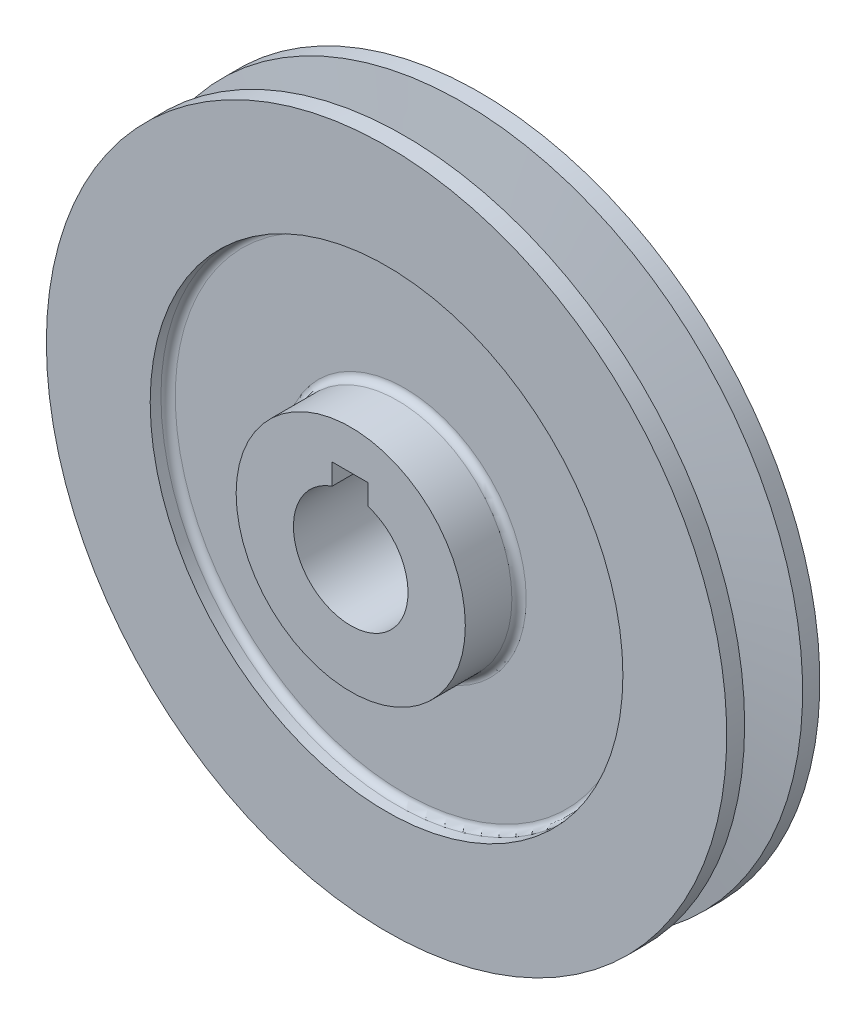
SolidWorks part; units mm, degrees
ref_plane "Front Plane" through (0, 0, 0) normal (0, 0, 1) x (1, 0, 0)
ref_plane "Top Plane" through (0, 0, 0) normal (0, 1, 0) x (1, 0, 0)
ref_plane "Right Plane" through (0, 0, 0) normal (1, 0, 0) x (0, 0, -1)
sketch "Sketch1" plane through (0, 0, 0) normal (0, 0, 1) x (1, 0, 0)
  circle A0 centre (0, 0) radius 47.5
  dimension "D1" = 95
extrude "Boss-Extrude1" add sketch "Sketch1" along normal blind 13
sketch "Sketch2" plane through (0, 0, 13) normal (0, 0, 1) x (1, 0, 0)
  circle A0 centre (0, 0) radius 33
  dimension "D1" = 66
extrude "Cut-Extrude1" cut sketch "Sketch2" against normal blind 2.5
sketch "Sketch3" plane through (0, 0, 0) normal (0, 0, -1) x (-1, 0, 0)
  circle A0 centre (0, 0) radius 33
  dimension "D1" = 66
extrude "Cut-Extrude2" cut sketch "Sketch3" against normal blind 2.5
sketch "Sketch4" plane through (0, 0, 2.5) normal (0, 0, -1) x (-1, 0, 0)
  circle A0 centre (0, 0) radius 16
  dimension "D1" = 32
extrude "Boss-Extrude2" add sketch "Sketch4" along normal blind 7.5
sketch "Sketch5" plane through (0, 0, 10.5) normal (0, 0, 1) x (1, 0, 0)
  circle A0 centre (0, 0) radius 16
  dimension "D1" = 32
extrude "Boss-Extrude3" add sketch "Sketch5" along normal blind 7.5
sketch "Sketch9" plane through (0, 0, -5) normal (0, 0, -1) x (-1, 0, 0)
  circle A0 centre (0, 0) radius 8
  dimension "D1" = 16
extrude "Cut-Extrude3" cut sketch "Sketch9" against normal through all
fillet "Fillet1" radius 1 1 edges at (-16, 0, 2.5)
fillet "Fillet2" radius 1 1 edges at (16, 0, 10.5)
sketch "Sketch12" plane through (0, 0, 0) normal (1, 0, 0) x (0, 0, -1)
  line L0 (-10.5, 47.5) -> (-8.5051, 33)
  line L1 (0, 47.5) -> (-13, 47.5) construction
  line L2 (-8.5051, 33) -> (-4.46, 33)
  line L3 (-4.46, 33) -> (-2.4034, 47.5)
  line L4 (-6.5, 33) -> (-6.5, 26.3279) construction
  line L8 (-31.2441, 0) -> (32.2598, 0) construction
  line L9 (-10.5, 47.5) -> (-2.4034, 47.5)
  dimension "D3" = 14.5
revolve "Cut-Revolve1" cut sketch "Sketch12" angle 360 about L8
sketch "Sketch13" plane through (0, 0, 0) normal (0, 0, 1) x (1, 0, 0)
  line L0 (0, 25.984) -> (0, 10.5) construction
  line L1 (2.4069, 5.5824) -> (-2.5931, 5.5824)
  line L2 (-2.5931, 10.5) -> (2.4069, 10.5)
  line L3 (-2.5931, 10.5) -> (-2.5931, 5.5824)
  line L5 (2.4069, 10.5) -> (2.4069, 5.5824)
  point P3 (0, 4.7462)
  dimension "D1" = 5
extrude "Cut-Extrude5" cut sketch "Sketch13" along normal blind 27 and the other way blind 17
fillet "Fillet3" radius 1 1 edges at (-33, 0, 2.5)
fillet "Fillet4" radius 1 1 edges at (33, 0, 10.5)
